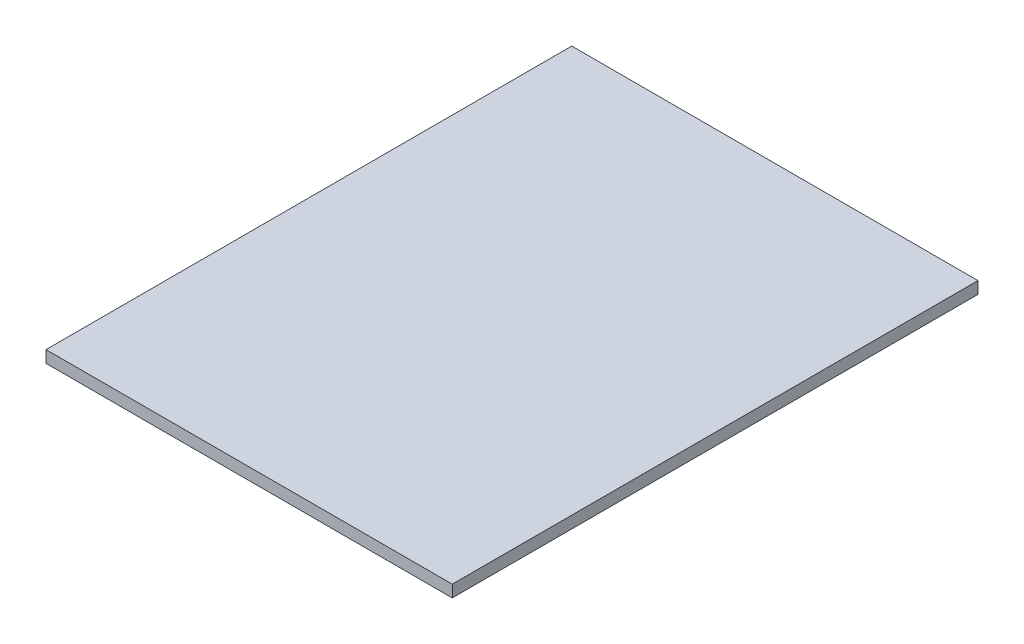
SolidWorks part; units mm, degrees
material "Oak"
ref_plane "Front Plane" through (0, 0, 0) normal (0, 0, 1) x (1, 0, 0)
ref_plane "Top Plane" through (0, 0, 0) normal (0, 1, 0) x (1, 0, 0)
ref_plane "Right Plane" through (0, 0, 0) normal (1, 0, 0) x (0, 0, -1)
sketch "Sketch1" plane through (0, 0, 0) normal (0, 1, 0) x (1, 0, 0)
  line L1 (-107.95, 139.7) -> (107.95, 139.7)
  line L2 (-107.95, 139.7) -> (-107.95, -139.7)
  line L3 (-107.95, -139.7) -> (107.95, -139.7)
  line L4 (107.95, 139.7) -> (107.95, -139.7)
  line L5 (-107.95, 139.7) -> (107.95, -139.7) construction
  line L6 (-107.95, -139.7) -> (107.95, 139.7) construction
  point P0 (0, 0)
  dimension "D1" = 215.9
  dimension "D2" = 279.4
extrude "Boss-Extrude1" add sketch "Sketch1" along normal mid plane 6.35
